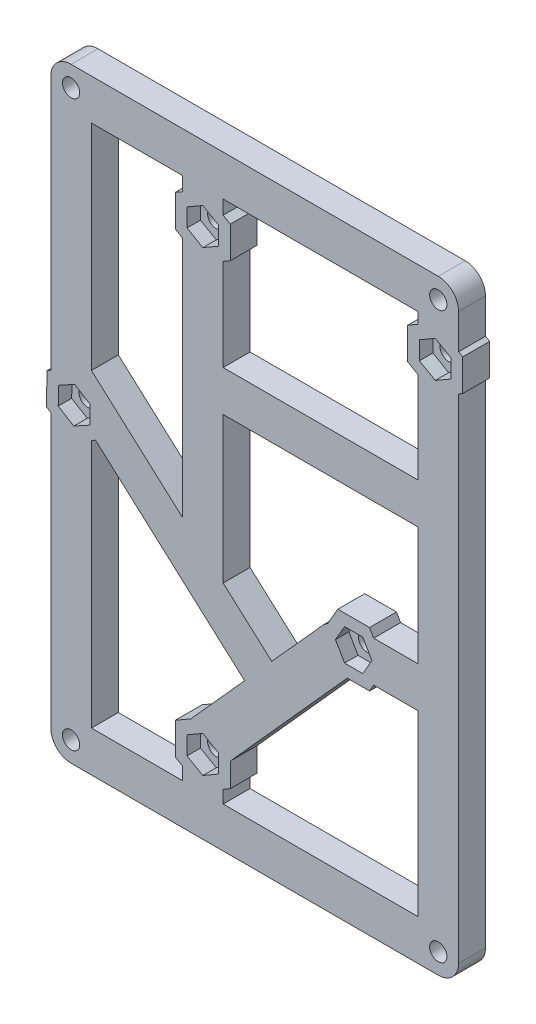
SolidWorks part; units mm, degrees
ref_plane "Front Plane" through (0, 0, 0) normal (0, 0, 1) x (1, 0, 0)
ref_plane "Top Plane" through (0, 0, 0) normal (0, 1, 0) x (1, 0, 0)
ref_plane "Right Plane" through (0, 0, 0) normal (1, 0, 0) x (0, 0, -1)
sketch "Sketch4" plane through (0, 0, 0) normal (0, 0, 1) x (1, 0, 0)
  line L0 (0, 0) -> (15.347, 0) construction
  circle A0 centre (-62.78, 96.55) radius 1.475
  circle A1 centre (0, 96.55) radius 1.475
  circle A2 centre (0, 0) radius 1.475
  circle A3 centre (-62.78, 0) radius 1.475
  circle A4 centre (-62.78, 96.55) radius 3.475
  circle A5 centre (0, 96.55) radius 3.475
  circle A6 centre (-62.78, 0) radius 3.475
  circle A7 centre (0, 0) radius 3.475
  dimension "D1" = 2.95
  dimension "D2" = 2.95
  dimension "D3" = 2.95
  dimension "D4" = 2.95
  dimension "D5" = 62.78
  dimension "D6" = 96.55
  dimension "D7" = 0
  dimension "D8" = 96.55
  dimension "D9" = 0
  dimension "D10" = 0
  dimension "D11" = 0
  dimension "D12" = 0
  dimension "D13" = 2
extrude "Boss-Extrude3" add sketch "Sketch4" along normal blind 2.3
sketch "Sketch2" plane through (0, 0, 0) normal (0, 0, 1) x (1, 0, 0)
  circle A0 centre (-40.26, 87.26) radius 1.475
  circle A1 centre (-40.26, 9.09) radius 1.475
  circle A2 centre (-14.46, 37.44) radius 1.475
  circle A3 centre (-0.52, 87.46) radius 1.475
  circle A4 centre (-14.46, 37.44) radius 3.475
  circle A5 centre (-0.52, 87.46) radius 3.475
  circle A6 centre (-40.26, 87.26) radius 3.475
  circle A7 centre (-40.26, 9.09) radius 3.475
  circle A8 centre (-62.78, 0) radius 3.475 construction
  circle A9 centre (-62.25, 49.81) radius 1.475
  circle A10 centre (-62.25, 49.81) radius 3.475
  dimension "D1" = 2.95
  dimension "D2" = 2.95
  dimension "D3" = 2.95
  dimension "D4" = 2.95
  dimension "D5" = 78.17
  dimension "D6" = 25.8
  dimension "D7" = 28.35
  dimension "D8" = 39.74
  dimension "D9" = 78.37
  dimension "D11" = 2.95
  dimension "D12" = 9.09
  dimension "D14" = 61.73
  dimension "D15" = 37.45
  dimension "62.78/2" = 22.52
  dimension "D10" = 2
  dimension "D13" = 2
extrude "Boss-Extrude4" add sketch "Sketch2" along normal blind 2.3 separate body
sketch "Sketch5" plane through (0, 0, 0) normal (0, 0, -1) x (-1, 0, 0)
  line L0 (-3.475, 96.55) -> (-3.475, 0)
  line L1 (3.475, 96.55) -> (3.475, 0)
  line L2 (0, -3.475) -> (62.78, -3.475)
  line L3 (0, 3.475) -> (62.78, 3.475)
  line L4 (66.255, 0) -> (66.255, 96.55)
  line L5 (59.305, 96.55) -> (59.305, 0)
  line L6 (62.78, 93.075) -> (0, 93.075)
  line L7 (0, 100.025) -> (62.78, 100.025)
  circle A0 centre (0, 96.55) radius 3.475 construction
  circle A1 centre (0, 0) radius 3.475 construction
  circle A2 centre (62.78, 0) radius 3.475 construction
  circle A3 centre (62.78, 96.55) radius 3.475 construction
  circle A4 centre (0, 96.55) radius 3.475
  circle A5 centre (62.78, 96.55) radius 3.475
  circle A6 centre (0, 0) radius 3.475
  circle A7 centre (62.78, 0) radius 3.475
  circle A8 centre (0, 96.55) radius 1.475
  circle A9 centre (0.52, 87.46) radius 1.475
  circle A10 centre (0, 0) radius 1.475
  circle A11 centre (62.78, 0) radius 1.475
  circle A12 centre (62.25, 49.81) radius 1.475
  circle A13 centre (62.78, 96.55) radius 1.475
  circle M1 centre (0, 96.55) radius 3.475
  circle M2 centre (0, 96.55) radius 1.475
extrude "Boss-Extrude8" add sketch "Sketch5" against normal up to surface (2.3 mm away) contours A6 L3 L1 L6 L0 A9 M1 | A5 L7 L1 L6 L5 M1 | A7 L4 A5 L6 L5 L3 A12 | A7 L5 L3 L1 A6 L2 | L6 L1 M1 | A5 L5 L6 | M1 M2 | A5 A13 | A6 A10 | A6 L1 L3 | A7 A11 | A7 L3 L5 up to face at (-58.775, 49.81, 2.3)
sketch "Sketch7" plane through (0, 0, 0) normal (0, 0, -1) x (-1, 0, 0)
  line L0 (43.735, 9.09) -> (43.735, 3.475)
  line L1 (3.475, 3.475) -> (59.305, 3.475) construction
  line L2 (36.785, 9.09) -> (36.785, 3.475)
  line L3 (36.785, 3.475) -> (43.735, 3.475)
  line L4 (14.46, 33.965) -> (3.475, 33.965)
  line L5 (3.475, 85.6314) -> (3.475, 3.475) construction
  line L6 (14.46, 40.915) -> (3.475, 40.915)
  line L7 (3.475, 40.915) -> (3.475, 33.965)
  line L8 (36.785, 87.26) -> (36.785, 93.075)
  line L9 (59.305, 93.075) -> (3.475, 93.075) construction
  line L10 (43.735, 87.26) -> (43.735, 93.075)
  line L11 (36.785, 93.075) -> (43.735, 93.075)
  circle A0 centre (40.26, 9.09) radius 3.475 construction
  circle A1 centre (14.46, 37.44) radius 3.475 construction
  circle A2 centre (14.46, 37.44) radius 3.475
  circle A3 centre (40.26, 9.09) radius 3.475
  circle A4 centre (40.26, 87.26) radius 3.475 construction
  circle A6 centre (14.46, 37.44) radius 1.475
  circle A7 centre (40.26, 9.09) radius 1.475
  circle A8 centre (40.26, 87.26) radius 1.475
  circle A9 centre (40.26, 87.26) radius 3.475
  circle M1 centre (40.26, 9.09) radius 3.475
extrude "Boss-Extrude9" add sketch "Sketch7" against normal up to surface (2.3 mm away) contours A9 L10 L11 L8 | A2 L6 L7 L4 | L2 L3 L0 M1 up to face at (-31.3888, 58.455, 2.3)
sketch "Sketch8" plane through (0, 0, 0) normal (0, 0, -1) x (-1, 0, 0)
  line L0 (14.46, 33.965) -> (36.785, 9.09)
  line L1 (14.46, 33.965) -> (19.6324, 38.6071)
  line L2 (36.785, 9.09) -> (41.9574, 13.7321)
  line L3 (19.6324, 38.6071) -> (41.9574, 13.7321)
  line L4 (14.46, 40.915) -> (3.475, 40.915) construction
  arc A0 (19.6324, 38.6071) -> (14.46, 40.915) centre (13.1383, 31.0027) ccw
  circle A1 centre (14.46, 37.44) radius 3.475 construction
  arc A2 (41.9574, 13.7321) -> (43.735, 9.09) centre (33.8005, 7.9471) cw
  circle A3 centre (40.26, 9.09) radius 3.475
  circle A4 centre (14.46, 37.44) radius 3.475
  arc M5 (14.46, 33.965) -> (14.46, 40.915) centre (14.46, 37.44) ccw
  arc M20 (43.735, 9.09) -> (36.785, 9.09) centre (40.26, 9.09) ccw
  dimension "D5" = 10
  dimension "D6" = 10
  dimension "D1" = 6.95
  dimension "D2" = 90
  dimension "D3" = 6.95
  dimension "D4" = 90
extrude "Boss-Extrude10" add sketch "Sketch8" against normal up to surface (2.3 mm away) contours L3 L1 L0 L2 M5 M20 | A2 L2 M20 | L1 A0 M5
sketch "Sketch9" plane through (0, 0, 0) normal (0, 0, -1) x (-1, 0, 0)
  line L0 (28.4738, 28.7558) -> (33.1159, 23.5834)
  line L1 (19.6324, 38.6071) -> (41.9574, 13.7321) construction
  line L2 (59.305, 56.4264) -> (59.305, 47.0878)
  line L3 (28.4738, 28.7558) -> (33.1159, 23.5834)
  line L4 (59.305, 93.075) -> (59.305, 51.6546) construction
  line L5 (28.4738, 28.7558) -> (65.4682, 61.9578)
  line L6 (33.1159, 23.5834) -> (72.9821, 59.3628)
  line L7 (59.305, 47.9654) -> (59.305, 3.475) construction
  line L8 (59.305, 47.0878) -> (59.305, 56.4264)
  line L9 (28.4738, 28.7558) -> (59.305, 56.4264)
  line M15 (59.305, 93.075) -> (59.305, 51.6546)
  arc M16 (59.305, 51.6546) -> (59.305, 47.9654) centre (62.25, 49.81) ccw
  line M17 (59.305, 47.9654) -> (59.305, 3.475)
  line M22 (41.9574, 13.7321) -> (19.6324, 38.6071)
  dimension "D1" = 6.95
  dimension "D5" = 90
  dimension "D6" = 90
extrude "Boss-Extrude11" add sketch "Sketch9" against normal up to surface (2.3 mm away) contours L6 L5 M22 M17 M16 M15 up to face at (-33.4403, 53.6511, 2.3)
sketch "Sketch10" plane through (0, 0, 0) normal (0, 0, -1) x (-1, 0, 0)
  line L0 (36.785, 87.26) -> (36.785, 36.215)
  line L1 (28.4738, 28.7558) -> (59.305, 56.4264) construction
  line L2 (43.735, 87.26) -> (43.735, 42.4525)
  line L3 (43.735, 42.4525) -> (36.785, 36.215)
  line L4 (36.785, 87.26) -> (43.735, 87.26)
  circle A0 centre (40.26, 87.26) radius 1.475
  line M9 (59.305, 56.4264) -> (28.4738, 28.7558)
  arc M19 (36.785, 87.26) -> (43.735, 87.26) centre (40.26, 87.26) ccw
extrude "Boss-Extrude12" add sketch "Sketch10" against normal up to surface (2.3 mm away) contours L2 L0 M19 M9 up to face at (-46.4135, 15.83, 2.3)
sketch "Sketch12" plane through (0, 0, 2.3) normal (0, 0, 1) x (1, 0, 0)
  line L0 (-36.785, 64.645) -> (-3.475, 64.645) construction
  line L1 (-36.785, 36.215) -> (-36.785, 93.075) construction
  line L2 (-3.475, 85.6314) -> (-3.475, 40.915) construction
  line L4 (-36.785, 61.17) -> (-3.475, 61.17)
  line L5 (-36.785, 61.17) -> (-36.785, 68.12)
  line L6 (-36.785, 68.12) -> (-3.475, 68.12)
  line L7 (-3.475, 61.17) -> (-3.475, 68.12)
  dimension "D1" = 6.95
  dimension "D2" = 3.475
extrude "Boss-Extrude13" add sketch "Sketch12" against normal up to surface (2.3 mm away) up to face at (-16.651, 58.7389, 0)
sketch "Sketch13" plane through (0, 0, 2.3) normal (0, 0, 1) x (1, 0, 0)
  line L13 (-11.3423, 37.44) -> (-12.9012, 40.14)
  line L14 (-12.9012, 40.14) -> (-16.0188, 40.14)
  line L15 (-16.0188, 40.14) -> (-17.5777, 37.44)
  line L16 (-17.5777, 37.44) -> (-16.0188, 34.74)
  line L17 (-16.0188, 34.74) -> (-12.9012, 34.74)
  line L18 (-12.9012, 34.74) -> (-11.3423, 37.44)
  line L49 (-40.26, 5.9723) -> (-37.56, 7.5312)
  line L50 (-37.56, 7.5312) -> (-37.56, 10.6488)
  line L51 (-37.56, 10.6488) -> (-40.26, 12.2077)
  line L52 (-40.26, 12.2077) -> (-42.96, 10.6488)
  line L53 (-42.96, 10.6488) -> (-42.96, 7.5312)
  line L54 (-42.96, 7.5312) -> (-40.26, 5.9723)
  line L55 (-40.26, 90.3777) -> (-42.96, 88.8188)
  line L56 (-42.96, 88.8188) -> (-42.96, 85.7012)
  line L57 (-42.96, 85.7012) -> (-40.26, 84.1423)
  line L58 (-40.26, 84.1423) -> (-37.56, 85.7012)
  line L59 (-37.56, 85.7012) -> (-37.56, 88.8188)
  line L60 (-37.56, 88.8188) -> (-40.26, 90.3777)
  line L61 (-0.52, 90.5777) -> (-3.22, 89.0188)
  line L62 (-3.22, 89.0188) -> (-3.22, 85.9012)
  line L63 (-3.22, 85.9012) -> (-0.52, 84.3423)
  line L64 (-0.52, 84.3423) -> (2.18, 85.9012)
  line L65 (2.18, 85.9012) -> (2.18, 89.0188)
  line L66 (2.18, 89.0188) -> (-0.52, 90.5777)
  circle A0 centre (-40.26, 87.26) radius 2.7 construction
  circle A1 centre (-0.52, 87.46) radius 2.7 construction
  circle A2 centre (-14.46, 37.44) radius 2.7 construction
  circle A3 centre (-40.26, 9.09) radius 2.7 construction
  point P11 (-42.96, 9.09)
  dimension "D1" = 5.4
  dimension "D2" = 5.4
  dimension "D3" = 5.4
  dimension "D4" = 5.4
extrude "Cut-Extrude1" cut sketch "Sketch13" against normal blind 10
sketch "Sketch16" plane through (0, 0, 0) normal (0, 0, -1) x (-1, 0, 0)
  line L0 (-0.83, 85.1217) -> (1.87, 89.7983)
  line L1 (0.52, 84.3423) -> (-2.18, 85.9012) construction
  line L2 (0.52, 90.5777) -> (3.22, 89.0188) construction
  line L3 (38.91, 84.9217) -> (41.61, 89.5983)
  line L4 (40.26, 84.1423) -> (37.56, 85.7012) construction
  line L5 (40.26, 90.3777) -> (42.96, 88.8188) construction
  line L6 (14.46, 34.74) -> (14.46, 40.14)
  line L7 (16.0188, 34.74) -> (12.9012, 34.74) construction
  line L8 (12.9012, 40.14) -> (16.0188, 40.14) construction
  line L9 (41.61, 11.4283) -> (38.91, 6.7517)
  line L10 (40.26, 12.2077) -> (42.96, 10.6488) construction
  line L11 (40.26, 5.9723) -> (37.56, 7.5312) construction
  circle A0 centre (0.52, 87.46) radius 1.475
  circle A1 centre (0.52, 87.46) radius 3.475
  circle A2 centre (40.26, 87.26) radius 1.475
  circle A3 centre (40.26, 87.26) radius 3.475
  circle A4 centre (14.46, 37.44) radius 1.475
  circle A5 centre (40.26, 9.09) radius 1.475
  circle A6 centre (14.46, 37.44) radius 3.475
  circle A7 centre (40.26, 9.09) radius 3.475
  dimension "D1" = 2.95
  dimension "D3" = 2.95
  dimension "D5" = 2.95
  dimension "D6" = 2.95
  dimension "D7" = 2
  dimension "D2" = 2
  dimension "D4" = 2
extrude "Boss-Extrude15" add sketch "Sketch16" along normal blind 2.3
sketch "Sketch17" plane through (0, 0, 2.3) normal (0, 0, 1) x (1, 0, 0)
  line L0 (-35.56, 6.3765) -> (-35.56, 11.8035)
  line L1 (-37.56, 85.7012) -> (-37.56, 88.8188)
  line L2 (-37.56, 88.8188) -> (-40.26, 90.3777)
  line L3 (-40.26, 90.3777) -> (-42.96, 88.8188)
  line L4 (-42.96, 88.8188) -> (-42.96, 85.7012)
  line L5 (-42.96, 85.7012) -> (-40.26, 84.1423)
  line L6 (-40.26, 84.1423) -> (-37.56, 85.7012)
  line L7 (-0.52, 84.3423) -> (2.18, 85.9012)
  line L8 (2.18, 85.9012) -> (2.18, 89.0188)
  line L9 (2.18, 89.0188) -> (-0.52, 90.5777)
  line L10 (-0.52, 90.5777) -> (-3.22, 89.0188)
  line L11 (-3.22, 89.0188) -> (-3.22, 85.9012)
  line L12 (-3.22, 85.9012) -> (-0.52, 84.3423)
  line L13 (-11.3423, 37.44) -> (-12.9012, 40.14)
  line L14 (-12.9012, 40.14) -> (-16.0188, 40.14)
  line L15 (-16.0188, 40.14) -> (-17.5777, 37.44)
  line L16 (-17.5777, 37.44) -> (-16.0188, 34.74)
  line L17 (-16.0188, 34.74) -> (-12.9012, 34.74)
  line L18 (-12.9012, 34.74) -> (-11.3423, 37.44)
  line L19 (-37.56, 7.5312) -> (-37.56, 10.6488)
  line L20 (-37.56, 10.6488) -> (-40.26, 12.2077)
  line L21 (-40.26, 12.2077) -> (-42.96, 10.6488)
  line L22 (-42.96, 10.6488) -> (-42.96, 7.5312)
  line L23 (-42.96, 7.5312) -> (-40.26, 5.9723)
  line L24 (-40.26, 5.9723) -> (-37.56, 7.5312)
  line L25 (-35.56, 11.8035) -> (-40.26, 14.5171)
  line L26 (-40.26, 14.5171) -> (-44.96, 11.8035)
  line L27 (-44.96, 11.8035) -> (-44.96, 6.3765)
  line L28 (-44.96, 6.3765) -> (-40.26, 3.6629)
  line L29 (-40.26, 3.6629) -> (-35.56, 6.3765)
  line L30 (-19.8871, 37.44) -> (-17.1735, 32.74)
  line L31 (-17.1735, 32.74) -> (-11.7465, 32.74)
  line L32 (-11.7465, 32.74) -> (-9.0329, 37.44)
  line L33 (-9.0329, 37.44) -> (-11.7465, 42.14)
  line L34 (-11.7465, 42.14) -> (-17.1735, 42.14)
  line L35 (-17.1735, 42.14) -> (-19.8871, 37.44)
  line L36 (-5.22, 84.7465) -> (-0.52, 82.0329)
  line L37 (-0.52, 82.0329) -> (4.18, 84.7465)
  line L38 (4.18, 84.7465) -> (4.18, 90.1735)
  line L39 (4.18, 90.1735) -> (-0.52, 92.8871)
  line L40 (-0.52, 92.8871) -> (-5.22, 90.1735)
  line L41 (-5.22, 90.1735) -> (-5.22, 84.7465)
  line L42 (-40.26, 81.8329) -> (-35.56, 84.5465)
  line L43 (-35.56, 84.5465) -> (-35.56, 89.9735)
  line L44 (-35.56, 89.9735) -> (-40.26, 92.6871)
  line L45 (-40.26, 92.6871) -> (-44.96, 89.9735)
  line L46 (-44.96, 89.9735) -> (-44.96, 84.5465)
  line L47 (-44.96, 84.5465) -> (-40.26, 81.8329)
  circle A0 centre (-40.26, 87.26) radius 2.7 construction
  circle A1 centre (-0.52, 87.46) radius 2.7 construction
  circle A2 centre (-14.46, 37.44) radius 2.7 construction
  circle A3 centre (-40.26, 9.09) radius 2.7 construction
  dimension "D1" = 2
extrude "Boss-Extrude16" add sketch "Sketch17" against normal up to surface (2.3 mm away) up to face at (-32.0114, 80.8128, 0)
sketch "Sketch18" plane through (0, 0, 0) normal (0, 0, -1) x (-1, 0, 0)
  circle A0 centre (62.25, 49.81) radius 1.475
  circle A1 centre (62.25, 49.81) radius 3.475
  dimension "D1" = 2
extrude "Boss-Extrude17" add sketch "Sketch18" along normal blind 2.3
sketch "Sketch19" plane through (0, 0, 2.3) normal (0, 0, 1) x (1, 0, 0)
  line L1 (-59.5185, 51.313) -> (-62.1859, 52.927)
  line L2 (-62.1859, 52.927) -> (-64.9174, 51.424)
  line L3 (-64.9174, 51.424) -> (-64.9815, 48.307)
  line L4 (-64.9815, 48.307) -> (-62.3141, 46.693)
  line L5 (-62.3141, 46.693) -> (-59.5826, 48.196)
  line L6 (-59.5826, 48.196) -> (-59.5185, 51.313)
  circle A0 centre (-62.25, 49.81) radius 2.7 construction
  dimension "D1" = 5.4
extrude "Cut-Extrude2" cut sketch "Sketch19" against normal blind 2.3
sketch "Sketch20" plane through (0, 0, 2.3) normal (0, 0, 1) x (1, 0, 0)
  line L0 (-57.6067, 47.0005) -> (-57.4952, 52.4264)
  line L1 (-59.5826, 48.196) -> (-59.5185, 51.313)
  line L2 (-59.5185, 51.313) -> (-62.1859, 52.927)
  line L3 (-62.1859, 52.927) -> (-64.9174, 51.424)
  line L4 (-64.9174, 51.424) -> (-64.9815, 48.307)
  line L5 (-64.9815, 48.307) -> (-62.3141, 46.693)
  line L6 (-62.3141, 46.693) -> (-59.5826, 48.196)
  line L7 (-57.4952, 52.4264) -> (-62.1385, 55.2359)
  line L8 (-62.1385, 55.2359) -> (-66.8933, 52.6195)
  line L9 (-66.8933, 52.6195) -> (-67.0048, 47.1936)
  line L10 (-67.0048, 47.1936) -> (-62.3615, 44.3841)
  line L11 (-62.3615, 44.3841) -> (-57.6067, 47.0005)
  circle A0 centre (-62.25, 49.81) radius 2.7 construction
  dimension "D1" = 2
extrude "Boss-Extrude18" add sketch "Sketch20" against normal blind 2.3
sketch "Sketch21" plane through (0, 0, 0) normal (0, 0, -1) x (-1, 0, 0)
  line L12 (66.8933, 52.6195) -> (66.255, 52.9707)
  line L13 (66.255, 52.9707) -> (66.255, 96.55)
  line L14 (62.78, 100.025) -> (0, 100.025)
  line L15 (-3.475, 96.55) -> (-3.475, 90.5806)
  line L16 (-3.475, 90.5806) -> (-4.18, 90.1735)
  line L17 (-4.18, 90.1735) -> (-4.18, 84.7465)
  line L18 (-4.18, 84.7465) -> (-3.475, 84.3394)
  line L19 (-3.475, 84.3394) -> (-3.475, 0)
  line L20 (0, -3.475) -> (62.78, -3.475)
  line L21 (66.255, 0) -> (66.255, 46.7399)
  line L22 (66.255, 46.7399) -> (67.0048, 47.1936)
  line L23 (67.0048, 47.1936) -> (66.8933, 52.6195)
  line L24 (66.8933, 52.6195) -> (66.255, 52.9707)
  line L25 (66.255, 52.9707) -> (66.255, 96.55)
  line L26 (62.78, 100.025) -> (0, 100.025)
  line L27 (-3.475, 96.55) -> (-3.475, 90.5806)
  line L28 (-3.475, 90.5806) -> (-4.18, 90.1735)
  line L29 (-4.18, 90.1735) -> (-4.18, 84.7465)
  line L30 (-4.18, 84.7465) -> (-3.475, 84.3394)
  line L31 (-3.475, 84.3394) -> (-3.475, 0)
  line L32 (0, -3.475) -> (62.78, -3.475)
  line L33 (66.255, 0) -> (66.255, 46.7399)
  line L34 (66.255, 46.7399) -> (67.0048, 47.1936)
  line L35 (67.0048, 47.1936) -> (66.8933, 52.6195)
  arc A4 (66.255, 96.55) -> (62.78, 100.025) centre (62.78, 96.55) ccw
  arc A5 (0, 100.025) -> (-3.475, 96.55) centre (0, 96.55) ccw
  arc A6 (-3.475, 0) -> (0, -3.475) centre (0, 0) ccw
  arc A7 (62.78, -3.475) -> (66.255, 0) centre (62.78, 0) ccw
  arc A8 (66.255, 96.55) -> (62.78, 100.025) centre (62.78, 96.55) ccw
  arc A9 (0, 100.025) -> (-3.475, 96.55) centre (0, 96.55) ccw
  arc A10 (-3.475, 0) -> (0, -3.475) centre (0, 0) ccw
  arc A11 (62.78, -3.475) -> (66.255, 0) centre (62.78, 0) ccw
  dimension "D1" = 0
sketch "Sketch22" plane through (0, 0, 0) normal (0, 0, -1) x (-1, 0, 0)
  line L0 (-3.475, 84.3394) -> (-3.475, 0) construction
  line L1 (-4.18, 84.7465) -> (-3.475, 84.3394) construction
  line L2 (-4.18, 90.1735) -> (-4.18, 84.7465) construction
  line L3 (-3.475, 96.55) -> (-3.475, 90.5806) construction
  line L4 (62.78, 100.025) -> (0, 100.025) construction
  line L5 (-3.475, 84.3394) -> (-3.475, 0)
  line L6 (-4.18, 84.7465) -> (-3.475, 84.3394)
  line L7 (-4.18, 90.1735) -> (-4.18, 84.7465)
  line L8 (-3.475, 96.55) -> (-3.475, 90.5806)
  line L9 (62.78, 100.025) -> (0, 100.025)
  line L10 (0, -3.475) -> (62.78, -3.475) construction
  line L11 (3.475, 3.475) -> (36.785, 3.475) construction
  line L12 (36.785, 5.6692) -> (36.785, 3.475) construction
  line L13 (35.56, 6.3765) -> (36.785, 5.6692) construction
  line L14 (35.56, 10.4549) -> (35.56, 6.3765) construction
  line L15 (43.735, 3.475) -> (59.305, 3.475) construction
  line L16 (43.735, 5.6692) -> (43.735, 3.475) construction
  line L17 (43.735, 5.6692) -> (44.96, 6.3765) construction
  line L18 (44.96, 6.3765) -> (44.96, 11.8035) construction
  line L19 (44.96, 11.8035) -> (42.1759, 13.411) construction
  line L20 (33.1159, 23.5834) -> (41.9574, 13.7321) construction
  line L21 (59.305, 46.066) -> (59.305, 3.475) construction
  line L22 (59.305, 46.066) -> (58.5992, 46.4544) construction
  line L23 (66.255, 0) -> (66.255, 46.7399) construction
  line L24 (66.255, 46.7399) -> (67.0048, 47.1936) construction
  line L25 (67.0048, 47.1936) -> (66.8933, 52.6195) construction
  line L26 (66.8933, 52.6195) -> (66.255, 52.9707) construction
  line L27 (43.735, 42.4525) -> (59.305, 56.4264) construction
  line L28 (43.735, 42.4525) -> (43.735, 83.8392) construction
  line L29 (33.1159, 23.5834) -> (58.5992, 46.4544) construction
  line L30 (3.475, 33.965) -> (3.475, 3.475) construction
  line L31 (15.5594, 32.74) -> (35.56, 10.4549) construction
  line L32 (11.7465, 32.74) -> (15.5594, 32.74) construction
  line L33 (11.0392, 33.965) -> (11.7465, 32.74) construction
  line L34 (11.0392, 33.965) -> (3.475, 33.965) construction
  line L35 (11.0392, 40.915) -> (3.475, 40.915) construction
  line L36 (11.7465, 42.14) -> (11.0392, 40.915) construction
  line L37 (17.1735, 42.14) -> (11.7465, 42.14) construction
  line L38 (18.8744, 39.194) -> (17.1735, 42.14) construction
  line L39 (19.6324, 38.6071) -> (28.4738, 28.7558) construction
  line L40 (28.4738, 28.7558) -> (36.785, 36.215) construction
  line L41 (36.785, 36.215) -> (36.785, 61.17) construction
  line L42 (3.475, 61.17) -> (36.785, 61.17) construction
  line L43 (3.475, 61.17) -> (3.475, 40.915) construction
  line L44 (36.785, 68.12) -> (3.475, 68.12) construction
  line L45 (3.475, 83.739) -> (3.475, 68.12) construction
  line L46 (5.22, 84.7465) -> (3.475, 83.739) construction
  line L47 (5.22, 84.7465) -> (5.22, 90.1735) construction
  line L48 (5.22, 90.1735) -> (3.475, 91.181) construction
  line L49 (3.475, 93.075) -> (3.475, 91.181) construction
  line L50 (36.785, 68.12) -> (36.785, 83.8392) construction
  line L51 (35.56, 84.5465) -> (36.785, 83.8392) construction
  line L52 (35.56, 89.9735) -> (35.56, 84.5465) construction
  line L53 (36.785, 90.6808) -> (35.56, 89.9735) construction
  line L54 (36.785, 90.6808) -> (36.785, 93.075) construction
  line L55 (36.785, 93.075) -> (3.475, 93.075) construction
  line L56 (43.735, 83.8392) -> (44.96, 84.5465) construction
  line L57 (44.96, 84.5465) -> (44.96, 89.9735) construction
  line L58 (44.96, 89.9735) -> (43.735, 90.6808) construction
  line L59 (43.735, 90.6808) -> (43.735, 93.075) construction
  line L60 (59.305, 93.075) -> (59.305, 56.4264) construction
  line L61 (59.305, 93.075) -> (43.735, 93.075) construction
  line L62 (66.255, 52.9707) -> (66.255, 96.55) construction
  line L63 (0, -3.475) -> (62.78, -3.475)
  line L64 (3.475, 3.475) -> (36.785, 3.475)
  line L65 (36.785, 5.6692) -> (36.785, 3.475)
  line L66 (35.56, 6.3765) -> (36.785, 5.6692)
  line L67 (35.56, 10.4549) -> (35.56, 6.3765)
  line L68 (43.735, 3.475) -> (59.305, 3.475)
  line L69 (43.735, 5.6692) -> (43.735, 3.475)
  line L70 (43.735, 5.6692) -> (44.96, 6.3765)
  line L71 (44.96, 6.3765) -> (44.96, 11.8035)
  line L72 (44.96, 11.8035) -> (42.1759, 13.411)
  line L73 (33.1159, 23.5834) -> (41.9574, 13.7321)
  line L74 (59.305, 46.066) -> (59.305, 3.475)
  line L75 (59.305, 46.066) -> (58.5992, 46.4544)
  line L76 (66.255, 0) -> (66.255, 46.7399)
  line L77 (66.255, 46.7399) -> (67.0048, 47.1936)
  line L78 (67.0048, 47.1936) -> (66.8933, 52.6195)
  line L79 (66.8933, 52.6195) -> (66.255, 52.9707)
  line L80 (43.735, 42.4525) -> (59.305, 56.4264)
  line L81 (43.735, 42.4525) -> (43.735, 83.8392)
  line L82 (33.1159, 23.5834) -> (58.5992, 46.4544)
  line L83 (3.475, 33.965) -> (3.475, 3.475)
  line L84 (15.5594, 32.74) -> (35.56, 10.4549)
  line L85 (11.7465, 32.74) -> (15.5594, 32.74)
  line L86 (11.0392, 33.965) -> (11.7465, 32.74)
  line L87 (11.0392, 33.965) -> (3.475, 33.965)
  line L88 (11.0392, 40.915) -> (3.475, 40.915)
  line L89 (11.7465, 42.14) -> (11.0392, 40.915)
  line L90 (17.1735, 42.14) -> (11.7465, 42.14)
  line L91 (18.8744, 39.194) -> (17.1735, 42.14)
  line L92 (19.6324, 38.6071) -> (28.4738, 28.7558)
  line L93 (28.4738, 28.7558) -> (36.785, 36.215)
  line L94 (36.785, 36.215) -> (36.785, 61.17)
  line L95 (3.475, 61.17) -> (36.785, 61.17)
  line L96 (3.475, 61.17) -> (3.475, 40.915)
  line L97 (36.785, 68.12) -> (3.475, 68.12)
  line L98 (3.475, 83.739) -> (3.475, 68.12)
  line L99 (5.22, 84.7465) -> (3.475, 83.739)
  line L100 (5.22, 84.7465) -> (5.22, 90.1735)
  line L101 (5.22, 90.1735) -> (3.475, 91.181)
  line L102 (3.475, 93.075) -> (3.475, 91.181)
  line L103 (36.785, 68.12) -> (36.785, 83.8392)
  line L104 (35.56, 84.5465) -> (36.785, 83.8392)
  line L105 (35.56, 89.9735) -> (35.56, 84.5465)
  line L106 (36.785, 90.6808) -> (35.56, 89.9735)
  line L107 (36.785, 90.6808) -> (36.785, 93.075)
  line L108 (36.785, 93.075) -> (3.475, 93.075)
  line L109 (43.735, 83.8392) -> (44.96, 84.5465)
  line L110 (44.96, 84.5465) -> (44.96, 89.9735)
  line L111 (44.96, 89.9735) -> (43.735, 90.6808)
  line L112 (43.735, 90.6808) -> (43.735, 93.075)
  line L113 (59.305, 93.075) -> (59.305, 56.4264)
  line L114 (59.305, 93.075) -> (43.735, 93.075)
  line L115 (66.255, 52.9707) -> (66.255, 96.55)
  line L116 (-3.475, 90.5806) -> (-4.18, 90.1735) construction
  line L117 (-3.475, 90.5806) -> (-4.18, 90.1735)
  arc A0 (0, 100.025) -> (-3.475, 96.55) centre (0, 96.55) ccw construction
  circle A1 centre (0, 96.55) radius 1.475
  circle A2 centre (0, 96.55) radius 1.475
  arc A3 (0, 100.025) -> (-3.475, 96.55) centre (0, 96.55) ccw
  circle A4 centre (0, 0) radius 1.475 construction
  arc A5 (-3.475, 0) -> (0, -3.475) centre (0, 0) ccw construction
  circle A6 centre (62.78, 0) radius 1.475 construction
  arc A7 (62.78, -3.475) -> (66.255, 0) centre (62.78, 0) ccw construction
  arc A8 (42.1759, 13.411) -> (41.9574, 13.7321) centre (33.8005, 7.9471) ccw construction
  circle A9 centre (40.26, 9.09) radius 3.475 construction
  circle A10 centre (62.25, 49.81) radius 3.475 construction
  circle A11 centre (14.46, 37.44) radius 3.475 construction
  arc A12 (19.6324, 38.6071) -> (18.8744, 39.194) centre (13.1383, 31.0027) ccw construction
  circle A13 centre (40.26, 87.26) radius 3.475 construction
  circle A14 centre (0.52, 87.46) radius 3.475 construction
  arc A15 (66.255, 96.55) -> (62.78, 100.025) centre (62.78, 96.55) ccw construction
  circle A16 centre (62.78, 96.55) radius 1.475 construction
  circle A17 centre (0, 0) radius 1.475
  arc A18 (-3.475, 0) -> (0, -3.475) centre (0, 0) ccw
  circle A19 centre (62.78, 0) radius 1.475
  arc A20 (62.78, -3.475) -> (66.255, 0) centre (62.78, 0) ccw
  arc A21 (42.1759, 13.411) -> (41.9574, 13.7321) centre (33.8005, 7.9471) ccw
  circle A22 centre (40.26, 9.09) radius 3.475
  circle A23 centre (62.25, 49.81) radius 3.475
  circle A24 centre (14.46, 37.44) radius 3.475
  arc A25 (19.6324, 38.6071) -> (18.8744, 39.194) centre (13.1383, 31.0027) ccw
  circle A26 centre (40.26, 87.26) radius 3.475
  circle A27 centre (0.52, 87.46) radius 3.475
  arc A28 (66.255, 96.55) -> (62.78, 100.025) centre (62.78, 96.55) ccw
  circle A29 centre (62.78, 96.55) radius 1.475
  point P0 (-4.18, 90.1735)
  dimension "D1" = 0
extrude "Boss-Extrude19" add sketch "Sketch22" along normal up to surface (2.3 mm away) up to face at (-3.995, 87.46, -2.3)
